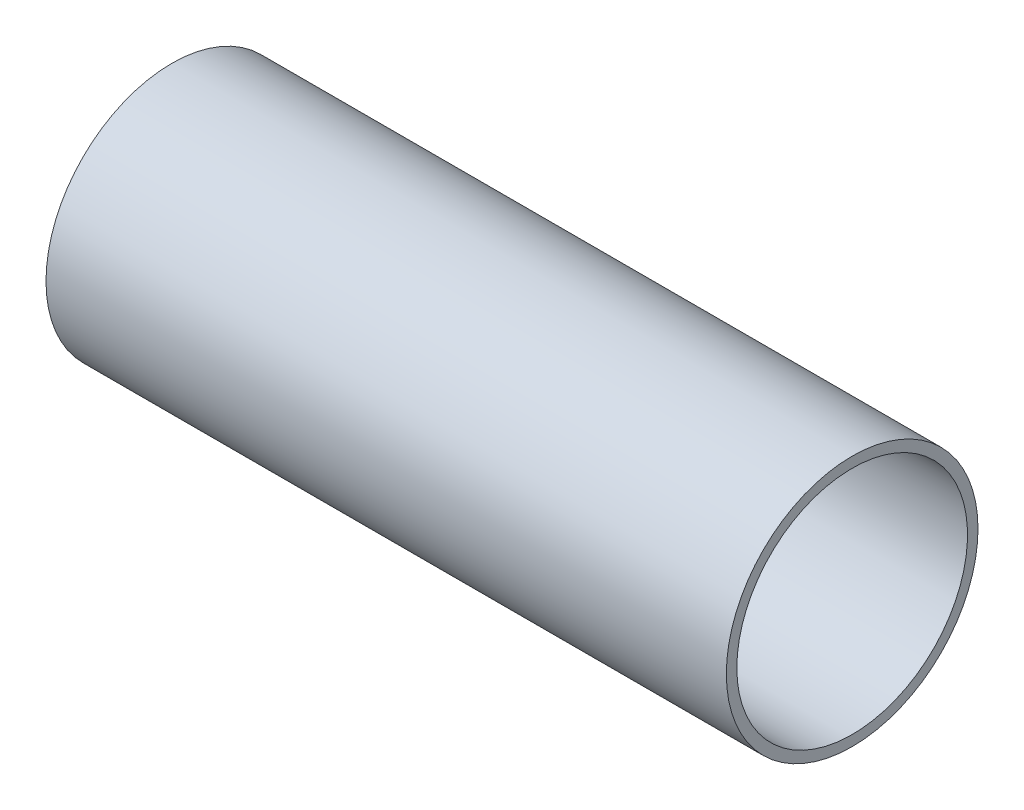
SolidWorks part; units mm, degrees
ref_plane "Front Plane" through (0, 0, 0) normal (0, 0, 1) x (1, 0, 0)
ref_plane "Top Plane" through (0, 0, 0) normal (0, 1, 0) x (1, 0, 0)
ref_plane "Right Plane" through (0, 0, 0) normal (1, 0, 0) x (0, 0, -1)
sketch "Sketch1" plane through (0, 0, 0) normal (0, 0, 1) x (1, 0, 0)
  line L0 (0, 0) -> (141124.8986, 0) construction
  line L1 (0, 0) -> (0, -141124.8986) construction
  line L2 (-206, 76.2) -> (206, 76.2)
  line L3 (206, 76.2) -> (206, 69.85)
  line L4 (206, 69.85) -> (-206, 69.85)
  line L5 (-206, 69.85) -> (-206, 76.2)
  point P7 (0, 69.85)
  dimension "D1" = 139.7
  dimension "D2" = 152.4
  dimension "D3" = 412
revolve "Revolve1" add sketch "Sketch1" angle 360 about L0
